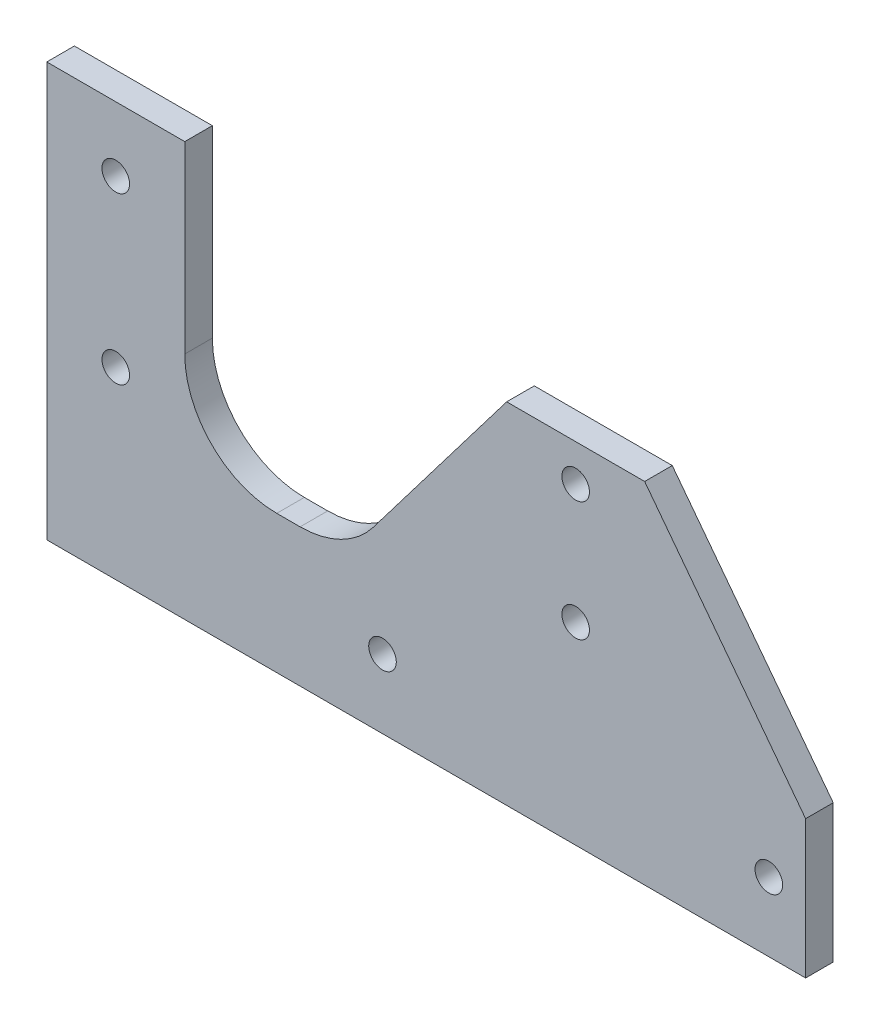
SolidWorks part; units mm, degrees
ref_plane "前视基准面" through (0, 0, 0) normal (0, 0, 1) x (1, 0, 0)
ref_plane "上视基准面" through (0, 0, 0) normal (0, 1, 0) x (1, 0, 0)
ref_plane "右视基准面" through (0, 0, 0) normal (1, 0, 0) x (0, 0, -1)
sketch "草图1" plane through (0, 0, 0) normal (0, 0, 1) x (1, 0, 0)
  line L0 (-7.5, 0) -> (7.5, 0)
  line L3 (25, -23) -> (25, -38)
  line L4 (25, -38) -> (-25, -38)
  line L5 (0, -38) -> (0, 14.3141) construction
  line L9 (-7.5, 0) -> (-21.9985, -19.0552)
  line L10 (-29.9568, -23) -> (-32.5, -23)
  line L11 (-42.5, -13) -> (-42.5, 7)
  line L12 (7.5, 0) -> (25, -23)
  line L13 (-42.5, 7) -> (-57.5, 7)
  line L14 (-57.5, 7) -> (-57.5, -38)
  line L15 (-57.5, -38) -> (-25, -38)
  arc A0 (-32.5, -23) -> (-42.5, -13) centre (-32.5, -13) cw
  arc A1 (-29.9568, -23) -> (-21.9985, -19.0552) centre (-29.9568, -13) ccw
  point P12 (0, 0)
  point P18 (-25, -23)
  dimension "D7" = 10
  dimension "D1" = 15
  dimension "D2" = 15
  dimension "D3" = 38
  dimension "D4" = 50
  dimension "D5" = 15
  dimension "D6" = 32.5
  dimension "D8" = 45
extrude "凸台-拉伸1" add sketch "草图1" along normal blind 3
sketch "草图2" plane through (0, 0, 3) normal (0, 0, 1) x (1, 0, 0)
  line L0 (7.5, 0) -> (-7.5, 0) construction
  line L2 (25, -38) -> (25, -23) construction
  line L4 (-57.5, 7) -> (-57.5, -38) construction
  line L5 (-42.5, 7) -> (-57.5, 7) construction
  line L6 (-57.5, -38) -> (25, -38) construction
  circle A0 centre (0, -4) radius 1.5
  circle A1 centre (0, -17) radius 1.5
  circle A2 centre (-21, -30.5) radius 1.5
  circle A5 centre (21, -30.5) radius 1.5
  circle A6 centre (-50, 0) radius 1.5
  circle A7 centre (-50, -18) radius 1.5
  point P8 (0, 0)
  point P9 (0, 0)
  point P24 (0, 0)
  point P25 (0, 0)
  dimension "D1" = 3
  dimension "D8" = 3
  dimension "D9" = 3
  dimension "D2" = 4
  dimension "D3" = 13
  dimension "D4" = 42
  dimension "D5" = 7.5
  dimension "D6" = 4
  dimension "D11" = 7.5
  dimension "D12" = 7
  dimension "D13" = 18
extrude "切除-拉伸1" cut sketch "草图2" against normal blind 3
